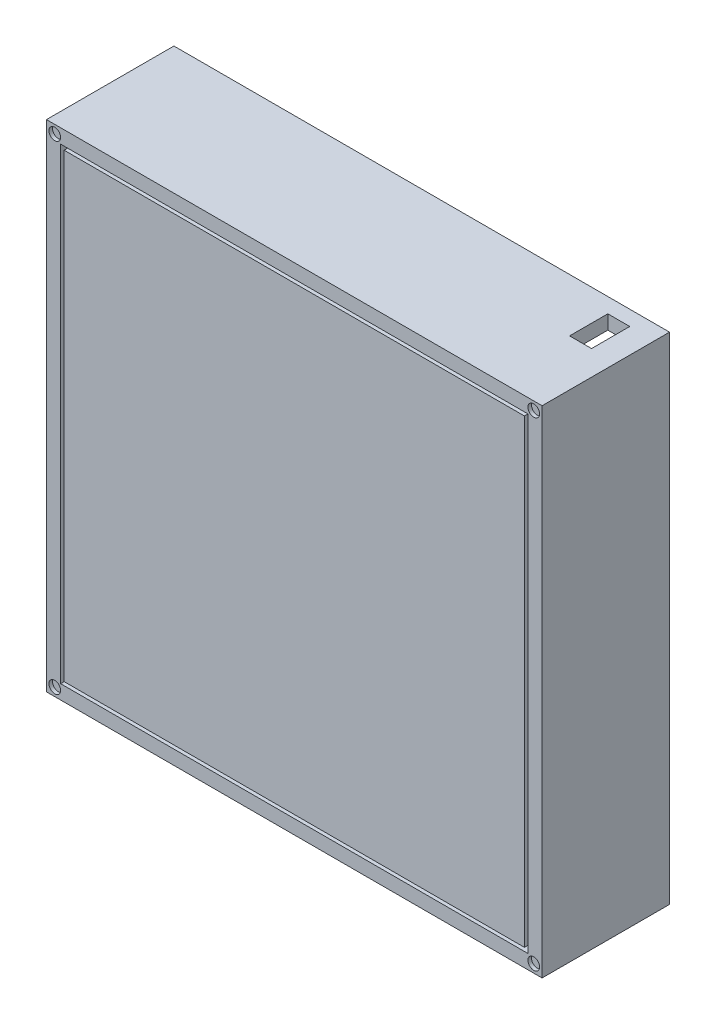
SolidWorks part; units mm, degrees
ref_plane "Front Plane" through (0, 0, 0) normal (0, 0, 1) x (1, 0, 0)
ref_plane "Top Plane" through (0, 0, 0) normal (0, 1, 0) x (1, 0, 0)
ref_plane "Right Plane" through (0, 0, 0) normal (1, 0, 0) x (0, 0, -1)
sketch "Sketch5" plane through (0, 0, 0) normal (0, 0, 1) x (1, 0, 0)
  line L1 (65, -65) -> (-65, -65)
  line L2 (65, -65) -> (65, 65)
  line L3 (65, 65) -> (-65, 65)
  line L4 (-65, -65) -> (-65, 65)
  line L5 (65, -65) -> (-65, 65) construction
  line L6 (65, 65) -> (-65, -65) construction
  point P0 (0, 0)
  dimension "D1" = 130
extrude "Boss-Extrude4" add sketch "Sketch5" along normal blind 10
ref_plane "Plane1" through (0, 0, 10) normal (0, 0, 1) x (1, 0, 0)
sketch "Sketch6" plane through (0, 0, 10) normal (0, 0, 1) x (1, 0, 0)
  line L1 (70, -70) -> (-70, -70)
  line L2 (70, -70) -> (70, 70)
  line L3 (70, 70) -> (-70, 70)
  line L4 (-70, -70) -> (-70, 70)
  line L5 (70, -70) -> (-70, 70) construction
  line L6 (70, 70) -> (-70, -70) construction
  line L7 (66, -66) -> (-66, -66)
  line L8 (66, -66) -> (66, 66)
  line L9 (66, 66) -> (-66, 66)
  line L10 (-66, -66) -> (-66, 66)
  line L11 (66, -66) -> (-66, 66) construction
  line L12 (66, 66) -> (-66, -66) construction
  point P0 (0, 0)
  point P6 (0, 0)
  dimension "D1" = 140
  dimension "D2" = 132
extrude "Boss-Extrude5" add sketch "Sketch6" against normal blind 36 separate body contours L2 L1 L4 L3 | L8 L7 L10 L9
sketch "Sketch7" plane through (0, 0, 10) normal (0, 0, 1) x (1, 0, 0)
  line L0 (66, 66) -> (70, 66) construction
  line L1 (0, -19.8) -> (0, 19.8) construction
  line L2 (19.8, 0) -> (-19.8, 0) construction
  line L3 (70, -70) -> (70, 70) construction
  line L4 (66, 66) -> (66, 70) construction
  line L5 (70, 70) -> (-70, 70) construction
  circle A0 centre (67.651, 67.651) radius 1.651
  circle A1 centre (-67.651, 67.651) radius 1.651
  circle A2 centre (67.651, -67.651) radius 1.651
  circle A3 centre (-67.651, -67.651) radius 1.651
  dimension "D1" = 3.302
extrude "Cut-Extrude2" cut sketch "Sketch7" against normal blind 1.02 contours A1 | A0 | A2 | A3
sketch "Sketch8" plane through (0, -70, 0) normal (0, -1, 0) x (1, 0, 0)
  line L0 (59, -30) -> (59, -26) construction
  line L4 (70, 10) -> (-70, 10)
  line L5 (-70, 10) -> (-70, -26)
  line L6 (-70, -26) -> (70, -26)
  line L7 (70, -26) -> (70, 10)
  line L8 (70, 10) -> (-70, 10) construction
  line L9 (-70, 10) -> (-70, -26) construction
  line L10 (-70, -26) -> (70, -26) construction
  line L11 (70, -26) -> (70, 10) construction
  line L14 (-59, 1.8) -> (-46, 1.8)
  line L15 (46, 1.8) -> (59, 1.8)
  line L16 (46, 1.8) -> (46, -26)
  line L17 (46, -26) -> (59, -26)
  line L18 (59, 1.8) -> (59, -26)
  line L19 (46, 1.8) -> (59, -26) construction
  line L20 (46, -26) -> (59, 1.8) construction
  line L22 (46.5, 1.3) -> (58.5, 1.3) construction
  line L23 (-59, 1.8) -> (-59, -26)
  line L24 (-59, -26) -> (-46, -26)
  line L25 (-46, 1.8) -> (-46, -26)
  line L26 (-59, 1.8) -> (-46, -26) construction
  line L27 (-59, -26) -> (-46, 1.8) construction
  point P8 (-64.5, -27.25)
  point P13 (52.5, -12.1)
  point P16 (-52.5, -12.1)
  line M15 (-70, -26) -> (70, -26)
  dimension "D2" = 13
  dimension "D3" = 13
  dimension "D4" = 0.5
  dimension "D5" = 0.5
  dimension "D6" = 0.5
  dimension "D1" = 0
extrude "Cut-Extrude3" cut sketch "Sketch8" against normal up to surface (4 mm away) contours L25 L14 L23 M15 | L18 L15 L16 L10 up to face at (0, -66, -8)
sketch "Sketch9" plane through (0, 70, 0) normal (0, 1, 0) x (1, 0, 0)
  line L0 (70, 26) -> (70, -10) construction
  line L1 (56.8, 10.9681) -> (63, 10.9681)
  line L2 (56.8, 10.9681) -> (56.8, 21.7681)
  line L3 (56.8, 21.7681) -> (63, 21.7681)
  line L4 (63, 10.9681) -> (63, 21.7681)
  line L5 (70, 26) -> (-70, 26) construction
  dimension "D1" = 6.2
  dimension "D2" = 10.8
  dimension "D3" = 7
  dimension "D4" = 4.2319
extrude "Cut-Extrude4" cut sketch "Sketch9" against normal blind 10 contours L2 L1 L4 L3
